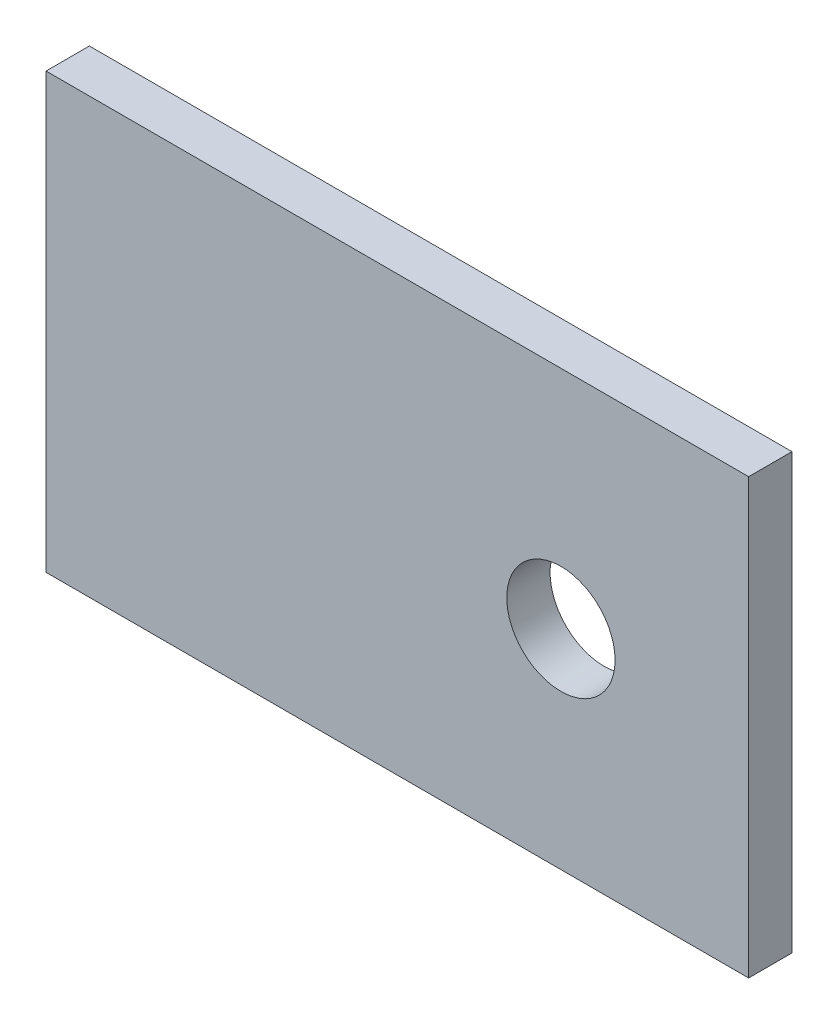
SolidWorks part; units mm, degrees
ref_plane "정면" through (0, 0, 0) normal (0, 0, 1) x (1, 0, 0)
ref_plane "윗면" through (0, 0, 0) normal (0, 1, 0) x (1, 0, 0)
ref_plane "우측면" through (0, 0, 0) normal (1, 0, 0) x (0, 0, -1)
sketch "스케치1" plane through (0, 0, 0) normal (0, 0, 1) x (1, 0, 0)
  line L1 (-23.7631, 10.4153) -> (8.6639, 10.4153)
  line L2 (-23.7631, 10.4153) -> (-23.7631, -9.6226)
  line L3 (-23.7631, -9.6226) -> (8.6639, -9.6226)
  line L4 (8.6639, 10.4153) -> (8.6639, -9.6226)
  circle A0 centre (0, 0) radius 2.5
  dimension "D1" = 5
extrude "보스-돌출1" add sketch "스케치1" along normal blind 2
